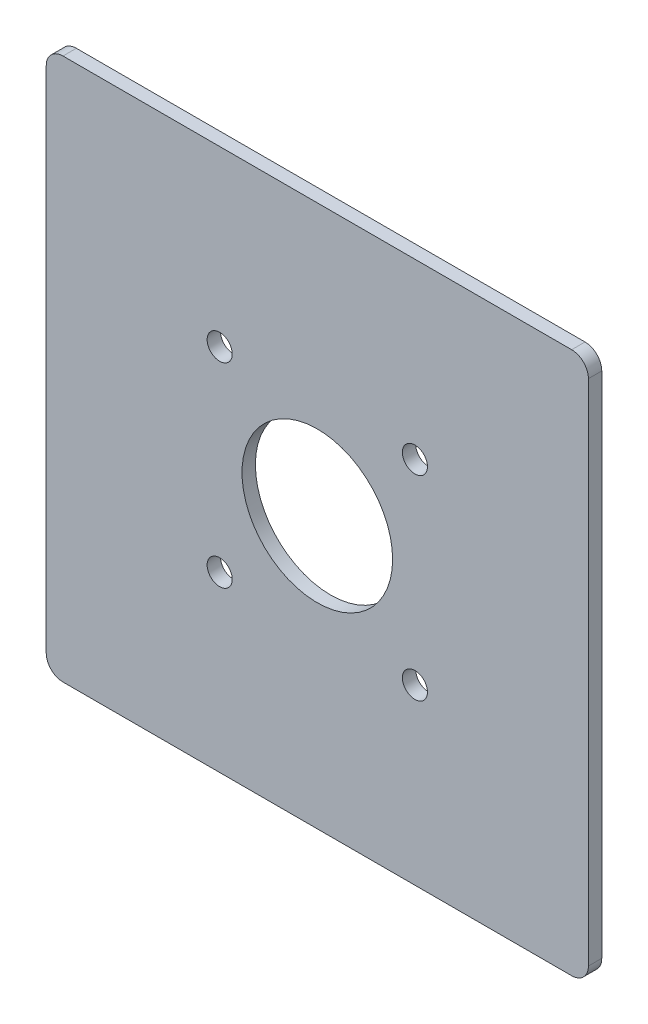
SolidWorks part; units mm, degrees
material "Plain Carbon Steel"
ref_plane "Front Plane" through (0, 0, 0) normal (0, 0, 1) x (1, 0, 0)
ref_plane "Top Plane" through (0, 0, 0) normal (0, 1, 0) x (1, 0, 0)
ref_plane "Right Plane" through (0, 0, 0) normal (1, 0, 0) x (0, 0, -1)
sketch "Sketch1" plane through (0, 0, 0) normal (0, 0, 1) x (1, 0, 0)
  line L1 (-162, -162) -> (162, -162)
  line L2 (-162, -162) -> (-162, 162)
  line L3 (-162, 162) -> (162, 162)
  line L4 (162, -162) -> (162, 162)
  line L5 (-162, -162) -> (162, 162) construction
  line L6 (-162, 162) -> (162, -162) construction
  point P0 (0, 0)
  dimension "D1" = 324
extrude "Boss-Extrude1" add sketch "Sketch1" along normal blind 8
sketch "Sketch2" plane through (0, 0, 8) normal (0, 0, 1) x (1, 0, 0)
  line L1 (-58.3363, -58.3363) -> (58.3363, -58.3363) construction
  line L2 (-58.3363, -58.3363) -> (-58.3363, 58.3363) construction
  line L3 (-58.3363, 58.3363) -> (58.3363, 58.3363) construction
  line L4 (58.3363, -58.3363) -> (58.3363, 58.3363) construction
  line L5 (-58.3363, -58.3363) -> (58.3363, 58.3363) construction
  line L6 (-58.3363, 58.3363) -> (58.3363, -58.3363) construction
  circle A1 centre (58.3363, 58.3363) radius 7.5
  circle A2 centre (0, 0) radius 82.5 construction
  point P0 (0, 0)
  dimension "D1" = 165
  dimension "D2" = 15
extrude "Cut-Extrude1" cut sketch "Sketch2" against normal blind 8
sketch "Sketch3" plane through (0, 0, 8) normal (0, 0, 1) x (1, 0, 0)
  circle A0 centre (0, 0) radius 45
  dimension "D1" = 90
extrude "Cut-Extrude2" cut sketch "Sketch3" against normal blind 10
pattern_circular "CirPattern1" count 4 over 360 about axis through (0, 0, 0) along (0, 0, 1) of "Cut-Extrude1"
fillet "Fillet1" radius 10 4 edges at (162, -162, 4) (162, 162, 4) (-162, 162, 4) (-162, -162, 4)
